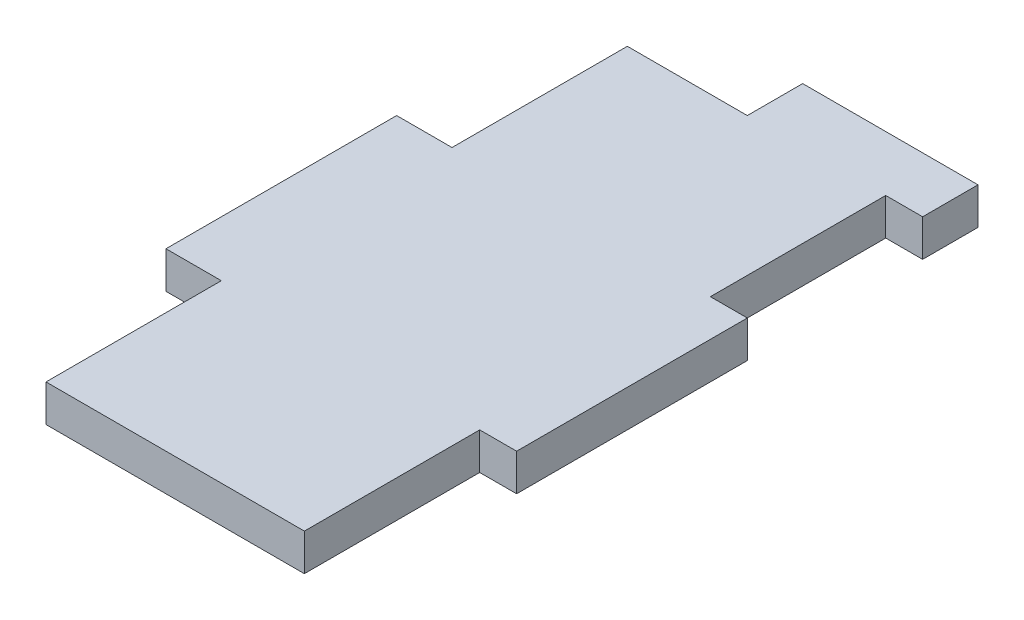
SolidWorks part; units mm, degrees
ref_plane "Front" through (0, 0, 0) normal (0, 0, 1) x (1, 0, 0)
ref_plane "Top" through (0, 0, 0) normal (0, 1, 0) x (1, 0, 0)
ref_plane "Right" through (0, 0, 0) normal (1, 0, 0) x (0, 0, -1)
sketch "Sketch1" plane through (0, 0, 0) normal (0, 1, 0) x (1, 0, 0)
  line L1 (0, 0) -> (38, 0)
  line L2 (0, 0) -> (0, 75)
  line L3 (0, 75) -> (38, 75)
  line L4 (38, 0) -> (38, 75)
  dimension "D1" = 38
  dimension "D2" = 75
extrude "Boss-Extrude1" add sketch "Sketch1" along normal blind 4
sketch "Sketch2" plane through (0, 4, 0) normal (0, 1, 0) x (1, 0, 0)
  line L0 (38, 75) -> (0, 75) construction
  line L1 (0, 0) -> (6, 0)
  line L2 (0, 0) -> (0, 25)
  line L3 (0, 25) -> (6, 25)
  line L4 (6, 0) -> (6, 25)
  line L5 (0, 25) -> (6, 25)
  line L6 (0, 25) -> (0, 50)
  line L7 (0, 50) -> (6, 50)
  line L8 (6, 25) -> (6, 50)
  line L9 (0, 50) -> (6, 50)
  line L10 (0, 50) -> (0, 75)
  line L11 (0, 75) -> (6, 75)
  line L12 (6, 50) -> (6, 75)
  line L13 (38, 0) -> (38, 75) construction
  line L14 (38, 75) -> (34, 75)
  line L15 (38, 75) -> (38, 50)
  line L16 (38, 50) -> (34, 50)
  line L17 (34, 75) -> (34, 50)
  line L18 (34, 50) -> (38, 50)
  line L19 (34, 50) -> (34, 25)
  line L20 (34, 25) -> (38, 25)
  line L21 (38, 50) -> (38, 25)
  line L22 (0, 0) -> (38, 0) construction
  line L23 (34, 25) -> (38, 25)
  line L24 (34, 25) -> (34, 0)
  line L25 (34, 0) -> (38, 0)
  line L26 (38, 25) -> (38, 0)
  line L28 (0, 75) -> (19, 75)
  line L29 (0, 75) -> (0, 69)
  line L30 (0, 69) -> (19, 69)
  line L31 (19, 75) -> (19, 69)
  line L32 (19, 69) -> (38, 69)
  line L33 (19, 69) -> (19, 75)
  line L34 (19, 75) -> (38, 75)
  line L35 (38, 69) -> (38, 75)
  line L44 (0, 0) -> (38, 0)
  line L45 (0, 0) -> (0, 6)
  line L46 (0, 6) -> (38, 6)
  line L47 (38, 0) -> (38, 6)
  dimension "D1" = 6
  dimension "D2" = 4
  dimension "D3" = 6
  dimension "D4" = 6
  dimension "D5" = 19
extrude "Cut-Extrude1" cut sketch "Sketch2" against normal through all
